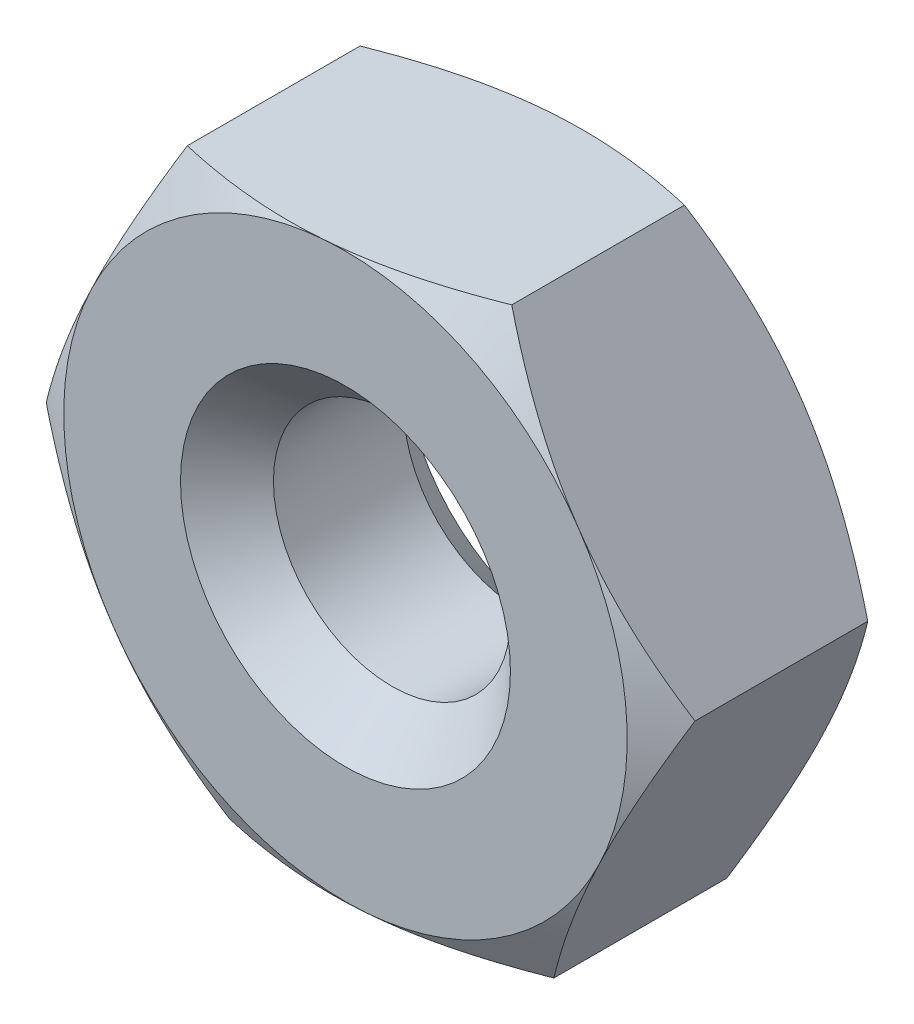
SolidWorks part; units mm, degrees
ref_plane "Přední rovina" through (0, 0, 0) normal (0, 0, 1) x (1, 0, 0)
ref_plane "Horní rovina" through (0, 0, 0) normal (0, 1, 0) x (1, 0, 0)
ref_plane "Pravá rovina" through (0, 0, 0) normal (1, 0, 0) x (0, 0, -1)
sketch "Skica1" plane through (0, 0, 0) normal (0, 0, 1) x (1, 0, 0)
  line L1 (1.5179, 3.1537) -> (-1.9722, 2.8914)
  line L2 (-1.9722, 2.8914) -> (-3.4902, -0.2623)
  line L3 (-3.4902, -0.2623) -> (-1.5179, -3.1537)
  line L4 (-1.5179, -3.1537) -> (1.9722, -2.8914)
  line L5 (1.9722, -2.8914) -> (3.4902, 0.2623)
  line L6 (3.4902, 0.2623) -> (1.5179, 3.1537)
  circle A0 centre (0, 0) radius 3.0311 construction
  circle A1 centre (0, 0) radius 1.275
  dimension "D1" = 7
  dimension "D2" = 2.55
extrude "Přidat vysunutím1" add sketch "Skica1" along normal blind 2.4
chamfer "Zkosení1" distance 0.5 angle 45 2 edges at (1.275, 0, 0) (1.275, 0, 2.4)
ref_plane "Rovina1" through (0, 0, 0) normal (0.4337, 0.9011, 0) x (0.9011, -0.4337, 0)
sketch3d "3DSkica1"
  line L0 (-2.7312, 1.3146, 2.4) -> (-2.7312, 1.3146, 0)
  line L1 (-2.7312, 1.3146, 2.4) -> (-2.7312, 1.3146, 0)
sketch "Skica3" plane through (0, 0, 0) normal (0.4337, 0.9011, 0) x (0.9011, -0.4337, 0)
  line L0 (-3.0311, -2.4) -> (-5.1095, -2.4)
  line L1 (-5.1095, -2.4) -> (-5.1095, 0)
  line L2 (-5.1095, 0) -> (-3.0311, 0)
  line L3 (-3.0311, 0) -> (-5.1095, -1.2)
  line L4 (-5.1095, -1.2) -> (-3.0311, -2.4)
  line L5 (0, -2.4) -> (0, -3.2676) construction
  dimension "D1" = 30
revolve "Odebrat rotací1" cut sketch "Skica3" angle 360 about L5
